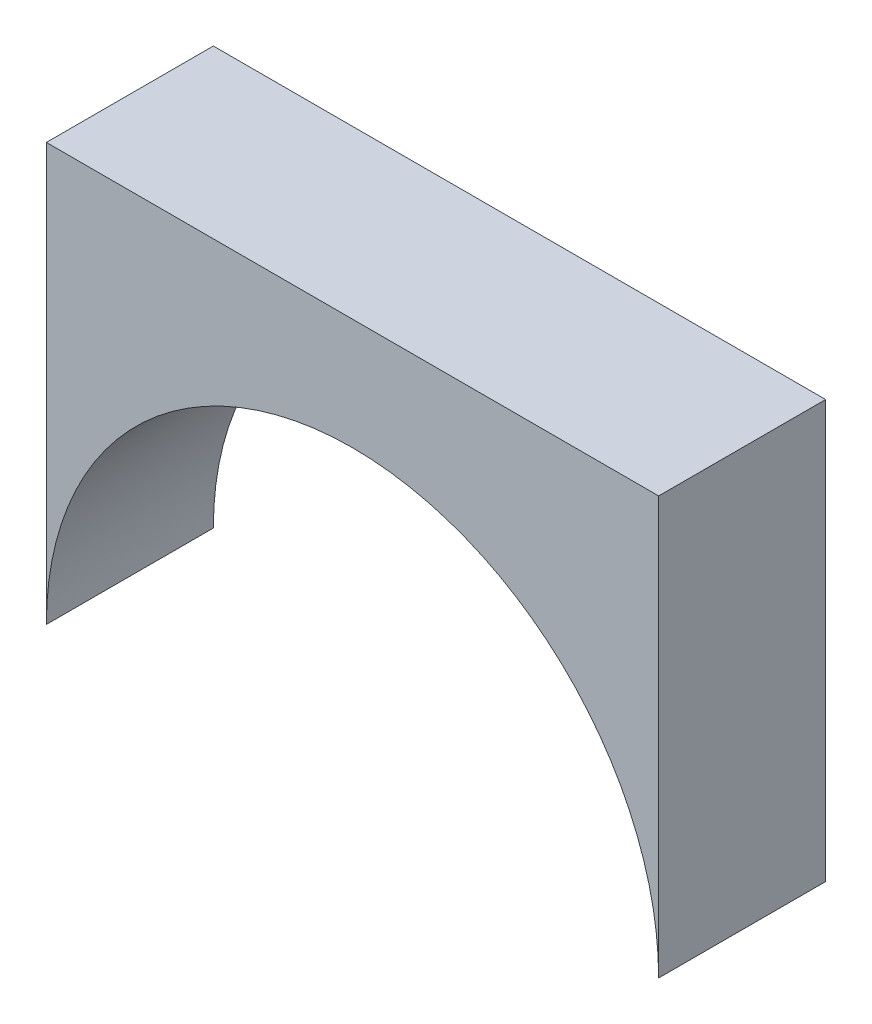
SolidWorks part; units mm, degrees
ref_plane "前视基准面" through (0, 0, 0) normal (0, 0, 1) x (1, 0, 0)
ref_plane "上视基准面" through (0, 0, 0) normal (0, 1, 0) x (1, 0, 0)
ref_plane "右视基准面" through (0, 0, 0) normal (1, 0, 0) x (0, 0, -1)
other "Configuration Table"
sketch "草图1" plane through (0, 0, 0) normal (0, 0, 1) x (1, 0, 0)
  line L0 (-5.5, 0) -> (-5.5, 7.5)
  line L1 (-5.5, 7.5) -> (5.5, 7.5)
  line L2 (5.5, 7.5) -> (5.5, 0)
  arc A0 (5.5, 0) -> (-5.5, 0) centre (0, 0) ccw
  dimension "D1" = 11
  dimension "D2" = 11
  dimension "D3" = 7.5
extrude "凸台-拉伸1" add sketch "草图1" along normal blind 3
